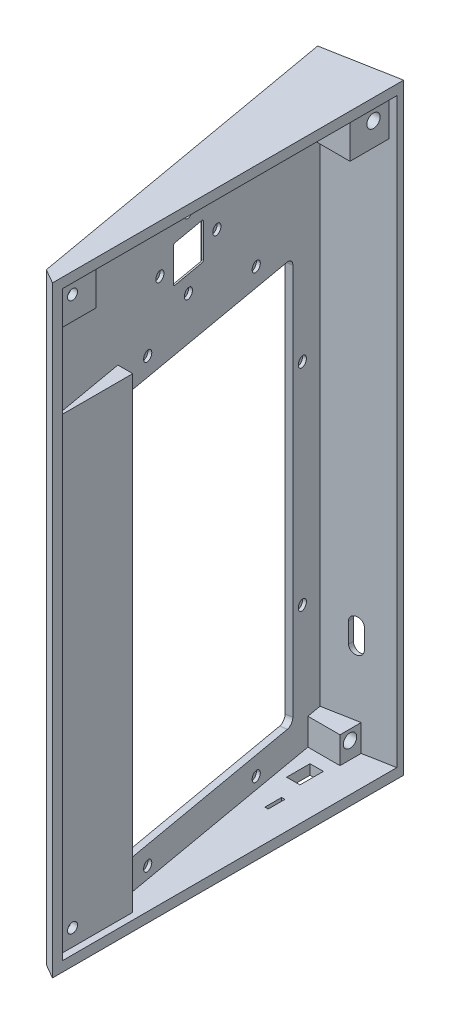
SolidWorks part; units mm, degrees
ref_plane "前视基准面" through (0, 0, 0) normal (0, 0, 1) x (1, 0, 0)
ref_plane "上视基准面" through (0, 0, 0) normal (0, 1, 0) x (1, 0, 0)
ref_plane "右视基准面" through (0, 0, 0) normal (1, 0, 0) x (0, 0, -1)
other "Configuration Table"
sketch "草图1" plane through (0, 0, 0) normal (0, 1, 0) x (1, 0, 0)
  line L0 (82.9035, -37.3993) -> (82.9035, -142.3993)
  line L1 (82.9035, -142.3993) -> (78.5734, -139.8993)
  line L2 (78.5734, -139.8993) -> (61.2086, -41.4185)
  line L3 (61.2086, -41.4185) -> (82.9035, -37.3993)
  dimension "D1" = 100
  dimension "D2" = 105
  dimension "D3" = 5
  dimension "D4" = 170
  dimension "D5" = 60
  dimension "D6" = 90.496
  dimension "D7" = 79.504
extrude "凸台-拉伸1" add sketch "草图1" along normal blind 180
sketch "草图5" plane through (52.2799, 0, -9.2184) normal (-0.9848, 0, 0.1736) x (0.1736, 0, 0.9848)
  line L0 (51.418, 180) -> (51.418, 0) construction
  line L1 (139.418, 12) -> (63.418, 12)
  line L2 (139.418, 12) -> (139.418, 133)
  line L3 (139.418, 133) -> (63.418, 133)
  line L4 (63.418, 12) -> (63.418, 133)
  line L5 (151.418, 180) -> (151.418, 0) construction
  line L6 (51.418, 0) -> (151.418, 0) construction
  dimension "D1" = 76
  dimension "D2" = 121
  dimension "D3" = 12
  dimension "D4" = 12
  dimension "D5" = 12
extrude "切除-拉伸2" cut sketch "草图5" against normal blind 2
sketch "草图7" plane through (82.9035, 0, 0) normal (1, 0, 0) x (0, 0, -1)
  line L8 (-139.3993, 3) -> (-40.3993, 3)
  line L9 (-40.3993, 3) -> (-40.3993, 177)
  line L10 (-40.3993, 177) -> (-139.3993, 177)
  line L11 (-139.3993, 177) -> (-139.3993, 3)
  line L12 (-139.3993, 3) -> (-40.3993, 3)
  line L13 (-40.3993, 3) -> (-40.3993, 177)
  line L14 (-40.3993, 177) -> (-139.3993, 177)
  line L15 (-139.3993, 177) -> (-139.3993, 3)
  dimension "D1" = 3
extrude "切除-拉伸3" cut sketch "草图7" against normal up to surface (19.8438 mm away)
sketch "草图10" plane through (54.2496, 0, -9.5657) normal (0.9848, 0, -0.1736) x (-0.1736, 0, -0.9848)
  line L1 (-63.418, 12) -> (-59.918, 12) construction
  line L2 (-63.418, 12) -> (-63.418, 41) construction
  line L3 (-63.418, 41) -> (-59.918, 41) construction
  line L4 (-59.918, 12) -> (-59.918, 41) construction
  line L5 (-63.418, 133) -> (-59.918, 133) construction
  line L6 (-63.418, 133) -> (-63.418, 104) construction
  line L7 (-63.418, 104) -> (-59.918, 104) construction
  line L8 (-59.918, 133) -> (-59.918, 104) construction
  circle A0 centre (-59.918, 104) radius 1.5
  circle A1 centre (-59.918, 41) radius 1.5
  dimension "D1" = 29
  dimension "D2" = 29
  dimension "D3" = 3.5
  dimension "D4" = 3.5
extrude "切除-拉伸5" cut sketch "草图10" against normal blind 1
sketch "草图11" plane through (54.2496, 0, -9.5657) normal (0.9848, 0, -0.1736) x (-0.1736, 0, -0.9848)
  line L0 (-76.918, 6.5) -> (-116.918, 6.5) construction
  line L1 (-63.418, 133) -> (-76.918, 133) construction
  line L2 (-63.418, 133) -> (-63.418, 138.5) construction
  line L3 (-63.418, 138.5) -> (-76.918, 138.5) construction
  line L4 (-76.918, 133) -> (-76.918, 138.5) construction
  line L5 (-63.418, 12) -> (-76.918, 12) construction
  line L6 (-63.418, 12) -> (-63.418, 6.5) construction
  line L7 (-63.418, 6.5) -> (-76.918, 6.5) construction
  line L8 (-76.918, 12) -> (-76.918, 6.5) construction
  line L9 (-76.918, 138.5) -> (-116.918, 138.5) construction
  circle A0 centre (-116.918, 138.5) radius 1.5
  circle A1 centre (-76.918, 138.5) radius 1.5
  circle A2 centre (-116.918, 6.5) radius 1.5
  circle A3 centre (-76.918, 6.5) radius 1.5
  dimension "D1" = 13.5
  dimension "D2" = 5.5
  dimension "D3" = 13.5
  dimension "D4" = 5.5
  dimension "D5" = 40
  dimension "D6" = 40
extrude "切除-拉伸6" cut sketch "草图11" against normal blind 1
sketch "草图12" plane through (82.9035, 0, 0) normal (1, 0, 0) x (0, 0, -1)
  line L1 (-139.3993, 3) -> (-116.3993, 3)
  line L2 (-139.3993, 3) -> (-139.3993, 142.5)
  line L3 (-139.3993, 142.5) -> (-116.3993, 142.5)
  line L4 (-116.3993, 3) -> (-116.3993, 142.5)
  line L6 (-127.7343, 133) -> (-52.8889, 133) construction
  dimension "D1" = 9.5
  dimension "D2" = 23
extrude "凸台-拉伸3" add sketch "草图12" against normal up to surface (2.3874 mm away)
sketch "草图13" plane through (54.2496, 0, -9.5657) normal (-0.9848, 0, 0.1736) x (0.1736, 0, 0.9848)
  line L4 (127.9081, 12) -> (139.418, 12)
  line L5 (139.418, 12) -> (139.418, 133)
  line L6 (139.418, 133) -> (127.9081, 133)
  line L7 (127.9081, 133) -> (127.9081, 12)
  line L8 (127.9081, 12) -> (139.418, 12)
  line L9 (139.418, 12) -> (139.418, 133)
  line L10 (139.418, 133) -> (127.9081, 133)
  line L11 (127.9081, 133) -> (127.9081, 12)
  dimension "D1" = 0
extrude "切除-拉伸7" cut sketch "草图13" against normal blind 2
sketch "草图14" plane through (52.2799, 0, -9.2184) normal (-0.9848, 0, 0.1736) x (0.1736, 0, 0.9848)
  line L0 (51.418, 180) -> (51.418, 0) construction
  line L1 (96.418, 151) -> (107.418, 151)
  line L2 (96.418, 151) -> (96.418, 162)
  line L3 (96.418, 162) -> (107.418, 162)
  line L4 (107.418, 151) -> (107.418, 162)
  line L5 (139.418, 133) -> (63.418, 133) construction
  line L6 (51.418, 180) -> (151.418, 180) construction
  dimension "D1" = 11
  dimension "D2" = 11
  dimension "D3" = 45
  dimension "D4" = 18
  dimension "D5" = 18
extrude "切除-拉伸8" cut sketch "草图14" against normal blind 2
sketch "草图17" plane through (9.4497, 0, 51.0074) normal (-0.1822, 0, -0.9833) x (-0.9833, 0, 0.1822)
  line L1 (-74.7037, 180) -> (-52.6396, 180)
  line L2 (-74.7037, 180) -> (-74.7037, 0)
  line L3 (-74.7037, 0) -> (-52.6396, 0)
  line L4 (-52.6396, 180) -> (-52.6396, 0)
extrude "凸台-拉伸9" add sketch "草图17" against normal blind 2
sketch "草图18" plane through (0, 0, 0) normal (0, -1, 0) x (1, 0, 0)
  line L0 (82.9035, 39.4333) -> (82.9035, 37.3993)
  line L1 (83.2679, 39.3658) -> (82.9035, 39.4333) construction
  line L2 (83.2679, 39.3658) -> (82.9035, 37.3993) construction
  line L3 (83.2679, 39.3658) -> (82.9035, 37.3993)
  line L4 (83.2679, 39.3658) -> (82.9035, 39.4333)
extrude "切除-拉伸9" cut sketch "草图18" against normal up to surface (180 mm away) up to face at (78.6267, 180, 73.3192)
sketch "草图19" plane through (0, 3, 0) normal (0, 1, 0) x (1, 0, 0)
  line L0 (82.9035, -40.3993) -> (82.9035, -36.7908) construction
  line L1 (77.596, -40.4166) -> (82.9035, -39.4333)
  line L2 (63.5225, -43.0238) -> (77.6894, -40.3993) construction
  line L3 (82.9035, -39.4333) -> (82.9035, -40.3993)
  line L4 (82.9035, -40.3993) -> (77.596, -40.4166)
extrude "切除-拉伸10" cut sketch "草图19" along normal up to surface (174 mm away) up to face at (77.507, 177, 80.5242)
sketch "草图20" plane through (82.9035, 0, 0) normal (1, 0, 0) x (0, 0, -1)
  line L1 (-139.3993, 142.5) -> (-116.3993, 142.5)
  line L2 (-139.3993, 142.5) -> (-139.3993, 3)
  line L3 (-139.3993, 3) -> (-116.3993, 3)
  line L4 (-116.3993, 142.5) -> (-116.3993, 3)
extrude "切除-拉伸11" cut sketch "草图20" against normal blind 2
sketch "草图21" plane through (54.2496, 0, -9.5657) normal (0.9848, 0, -0.1736) x (-0.1736, 0, -0.9848)
  line L0 (-107.418, 156.5) -> (-112.418, 156.5) construction
  line L1 (-107.418, 151) -> (-107.418, 162) construction
  line L2 (-101.918, 162) -> (-101.918, 167) construction
  line L3 (-107.418, 162) -> (-96.418, 162) construction
  line L4 (-96.418, 156.5) -> (-91.418, 156.5) construction
  line L5 (-96.418, 162) -> (-96.418, 151) construction
  line L6 (-101.918, 151) -> (-101.918, 146) construction
  line L7 (-96.418, 151) -> (-107.418, 151) construction
  circle A0 centre (-112.418, 156.5) radius 1.5
  circle A1 centre (-91.418, 156.5) radius 1.5
  circle A2 centre (-101.918, 146) radius 1.5
  circle A3 centre (-101.918, 167) radius 1.5
  dimension "D1" = 5
extrude "切除-拉伸12" cut sketch "草图21" against normal blind 1
sketch "草图23" plane through (80.9035, 0, 0) normal (1, 0, 0) x (0, 0, -1)
  line L0 (-51.4333, 8) -> (-51.4333, 26.4031) construction
  line L1 (-139.3993, 3) -> (-127.3993, 3)
  line L2 (-139.3993, 3) -> (-139.3993, 15)
  line L3 (-139.3993, 15) -> (-127.3993, 15)
  line L4 (-127.3993, 3) -> (-127.3993, 15)
  line L5 (-39.4333, 177) -> (-139.3993, 177) construction
  line L11 (-51.4333, 165) -> (-39.4333, 165)
  line L12 (-51.4333, 165) -> (-51.4333, 177)
  line L13 (-51.4333, 177) -> (-39.4333, 177)
  line L14 (-39.4333, 165) -> (-39.4333, 177)
  line L15 (-127.3993, 8) -> (-127.3993, 23.4787) construction
  line L17 (-127.3993, 165) -> (-139.3993, 165)
  line L18 (-127.3993, 165) -> (-127.3993, 177)
  line L19 (-127.3993, 177) -> (-139.3993, 177)
  line L20 (-139.3993, 165) -> (-139.3993, 177)
  dimension "D1" = 12
  dimension "D2" = 12
  dimension "D5" = 0
  dimension "D6" = 12
  dimension "D7" = 12
  dimension "D8" = 12
  dimension "D9" = 12
  dimension "D11" = 0
extrude "凸台-拉伸10" add sketch "草图23" against normal up to surface (0.3874 mm away)
fillet "圆角4" radius 2 5 edges at (64.2772, 133, 53.0625) (78.4592, 133, 127.7343) (64.2772, 12, 53.0625) (77.4744, 12, 127.9079) (80.394, 12, 127.3931)
sketch "草图26" plane through (0, 177, 0) normal (0, 1, 0) x (1, 0, 0)
  line L3 (63.1752, -41.0542) -> (71.9242, -39.4333)
  line L4 (71.9242, -39.4333) -> (62.8894, -39.4333)
  line L5 (62.8894, -39.4333) -> (63.1752, -41.0542)
  line L6 (63.1752, -41.0542) -> (71.9242, -39.4333)
  line L7 (71.9242, -39.4333) -> (62.8894, -39.4333)
  line L8 (62.8894, -39.4333) -> (63.1752, -41.0542)
  dimension "D1" = 0
extrude "切除-拉伸15" cut sketch "草图26" against normal up to next
sketch "草图27" plane through (82.9035, 0, 0) normal (1, 0, 0) x (0, 0, -1)
  line L1 (-39.4333, 3) -> (-47.4333, 3)
  line L2 (-39.4333, 3) -> (-39.4333, 11)
  line L3 (-39.4333, 11) -> (-47.4333, 11)
  line L4 (-47.4333, 3) -> (-47.4333, 11)
  dimension "D1" = 8
  dimension "D2" = 8
extrude "凸台-拉伸11" add sketch "草图27" against normal up to surface (18.6035 mm away)
sketch "草图28" plane through (82.9035, 0, 0) normal (1, 0, 0) x (0, 0, -1)
  line L1 (-47.4333, 3) -> (-39.4333, 3)
  line L2 (-47.4333, 3) -> (-47.4333, 11)
  line L3 (-47.4333, 11) -> (-39.4333, 11)
  line L4 (-39.4333, 3) -> (-39.4333, 11)
extrude "切除-拉伸16" cut sketch "草图28" against normal blind 9
sketch "草图29" plane through (0, 11, 0) normal (0, -1, 0) x (1, 0, 0)
  line L3 (73.9035, 41.1006) -> (73.9035, 39.4333)
  line L4 (73.9035, 39.4333) -> (82.9035, 39.4333)
  line L5 (82.9035, 39.4333) -> (73.9035, 41.1006)
  line L6 (73.9035, 41.1006) -> (73.9035, 39.4333)
  line L7 (73.9035, 39.4333) -> (82.9035, 39.4333)
  line L11 (82.9035, 39.4333) -> (73.9035, 41.1006)
  dimension "D1" = 0
extrude "凸台-拉伸12" add sketch "草图29" along normal up to surface (8 mm away) up to face at (77.0227, 3, 85.6663)
sketch "草图30" plane through (0, 3, 0) normal (0, -1, 0) x (1, 0, 0)
  line L3 (71.9242, 39.4333) -> (63.1752, 41.0542)
  line L4 (63.1752, 41.0542) -> (62.8894, 39.4333)
  line L5 (62.8894, 39.4333) -> (71.9242, 39.4333)
  line L6 (71.9242, 39.4333) -> (63.1752, 41.0542)
  line L7 (63.1752, 41.0542) -> (62.8894, 39.4333)
  line L8 (62.8894, 39.4333) -> (71.9242, 39.4333)
  dimension "D1" = 0
extrude "切除-拉伸17" cut sketch "草图30" against normal up to next
sketch "草图31" plane through (0, 0, 0) normal (0, -1, 0) x (1, 0, 0)
  line L1 (82.9035, 37.3993) -> (68.9035, 37.3993) construction
  line L2 (82.9035, 37.3993) -> (82.9035, 51.3993) construction
  line L3 (82.9035, 51.3993) -> (68.9035, 51.3993) construction
  line L4 (68.9035, 37.3993) -> (68.9035, 51.3993) construction
  line L5 (68.9035, 51.3993) -> (72.9035, 51.3993)
  line L6 (68.9035, 51.3993) -> (68.9035, 58.3993)
  line L7 (68.9035, 58.3993) -> (72.9035, 58.3993)
  line L8 (72.9035, 51.3993) -> (72.9035, 58.3993)
  dimension "D1" = 14
  dimension "D2" = 14
  dimension "D3" = 7
  dimension "D4" = 4
extrude "切除-拉伸18" cut sketch "草图31" against normal up to next
ref_plane "基准面1" through (0, 0, 37.3993) normal (0, 0, -1) x (-1, 0, 0)
ref_plane "基准面2" through (0, 0, 39.7193) normal (0, 0, -1) x (-1, 0, 0)
sketch "草图32" plane through (0, 0, 39.7193) normal (0, 0, -1) x (-1, 0, 0)
  line L0 (-72.7086, 36) -> (-72.7086, 30) construction
  line L1 (-70.7086, 36) -> (-70.7086, 30)
  line L2 (-74.7086, 36) -> (-74.7086, 30)
  line L3 (-82.9035, 180) -> (-61.2086, 180) construction
  line L4 (-61.2086, 180) -> (-61.2086, 0) construction
  arc A0 (-70.7086, 36) -> (-74.7086, 36) centre (-72.7086, 36) ccw
  arc A1 (-74.7086, 30) -> (-70.7086, 30) centre (-72.7086, 30) ccw
  point P2 (-72.7086, 33)
  point P9 (-72.7086, 28)
  point P10 (-72.7086, 38)
  dimension "D1" = 147
  dimension "D2" = 10
  dimension "D3" = 4
  dimension "D4" = 9.5
extrude "切除-拉伸23" cut sketch "草图32" against normal up to surface (1.9733 mm away)
ref_plane "基准面4" through (0, 0, 40.2193) normal (0, 0, -1) x (-1, 0, 0)
sketch "草图35" plane through (0, 0, 40.2193) normal (0, 0, -1) x (-1, 0, 0)
  line L0 (-74.7086, 36) -> (-74.7086, 30) construction
  line L1 (-76.7086, 41) -> (-68.7086, 41)
  line L2 (-76.7086, 41) -> (-76.7086, 25)
  line L3 (-76.7086, 25) -> (-68.7086, 25)
  line L4 (-68.7086, 41) -> (-68.7086, 25)
  line L5 (-70.7086, 30) -> (-70.7086, 36) construction
  arc A0 (-70.7086, 36) -> (-74.7086, 36) centre (-72.7086, 36) ccw construction
  arc A1 (-74.7086, 30) -> (-70.7086, 30) centre (-72.7086, 30) ccw construction
  dimension "D1" = 5
  dimension "D2" = 5
  dimension "D3" = 2
  dimension "D4" = 2
extrude "切除-拉伸25" cut sketch "草图35" along normal up to surface (0.1902 mm away)
fillet "圆角5" radius 0.5 4 edges at (76.7086, 25, 39.3831) (76.7086, 41, 39.3831) (68.7086, 25, 40.1241) (68.7086, 41, 40.1241)
sketch "草图36" plane through (0, 0, 0) normal (0, -1, 0) x (1, 0, 0)
  line L1 (82.9035, 37.3993) -> (74.4035, 37.3993) construction
  line L2 (82.9035, 37.3993) -> (82.9035, 64.3993) construction
  line L3 (82.9035, 64.3993) -> (74.4035, 64.3993) construction
  line L4 (74.4035, 37.3993) -> (74.4035, 64.3993) construction
  line L5 (74.4035, 64.3993) -> (73.4035, 64.3993)
  line L6 (74.4035, 64.3993) -> (74.4035, 69.3993)
  line L7 (74.4035, 69.3993) -> (73.4035, 69.3993)
  line L8 (73.4035, 64.3993) -> (73.4035, 69.3993)
  dimension "D1" = 8.5
  dimension "D2" = 27
  dimension "D3" = 1
  dimension "D4" = 5
extrude "切除-拉伸26" cut sketch "草图36" against normal up to next
sketch "草图37" plane through (0, 0, 0) normal (0, -1, 0) x (1, 0, 0)
  line L0 (73.4035, 66.8993) -> (74.4035, 66.8993) construction
  line L1 (73.4035, 69.3993) -> (73.4035, 64.3993) construction
  line L2 (74.4035, 64.3993) -> (74.4035, 69.3993) construction
  line L3 (73.9035, 64.3993) -> (73.9035, 69.3993) construction
  line L4 (73.4035, 64.3993) -> (74.4035, 64.3993) construction
  line L5 (74.4035, 69.3993) -> (73.4035, 69.3993) construction
  line L7 (74.9035, 69.8993) -> (72.9035, 69.8993)
  line L8 (74.9035, 69.8993) -> (74.9035, 63.8993)
  line L9 (74.9035, 63.8993) -> (72.9035, 63.8993)
  line L10 (72.9035, 69.8993) -> (72.9035, 63.8993)
  line L11 (74.9035, 69.8993) -> (72.9035, 63.8993) construction
  line L12 (74.9035, 63.8993) -> (72.9035, 69.8993) construction
  point P12 (73.9035, 66.8993)
  dimension "D1" = 6
  dimension "D2" = 2
extrude "切除-拉伸27" cut sketch "草图37" against normal blind 1
sketch "草图38" plane through (73.9035, 0, 0) normal (1, 0, 0) x (0, 0, -1)
  line L0 (-47.4333, 3) -> (-41.1006, 3) construction
  line L1 (-47.4333, 11) -> (-44.4333, 11) construction
  line L2 (-47.4333, 11) -> (-47.4333, 8) construction
  line L3 (-47.4333, 8) -> (-44.4333, 8) construction
  line L4 (-44.4333, 11) -> (-44.4333, 8) construction
  line L5 (-47.4333, 11) -> (-47.4333, 3) construction
  circle A0 centre (-44.4333, 8) radius 2
  dimension "D1" = 5
  dimension "D2" = 3
extrude "切除-拉伸28" cut sketch "草图38" against normal blind 3 contours A0
sketch "草图39" plane through (80.9035, 0, 0) normal (1, 0, 0) x (0, 0, -1)
  line L0 (-47.4333, 10.1358) -> (-47.4333, 2.8866) construction
  line L4 (-39.8038, 177) -> (-51.4333, 177) construction
  line L5 (-47.4333, 169) -> (-39.8038, 169) construction
  line L6 (-47.4333, 169) -> (-47.4333, 177) construction
  line L7 (-47.4333, 177) -> (-39.8038, 177) construction
  line L8 (-39.8038, 169) -> (-39.8038, 177) construction
  line L10 (-47.4333, 169) -> (-44.4333, 169) construction
  line L11 (-47.4333, 169) -> (-47.4333, 172) construction
  line L12 (-47.4333, 172) -> (-44.4333, 172) construction
  line L13 (-44.4333, 169) -> (-44.4333, 172) construction
  circle A0 centre (-44.4333, 172) radius 2
  dimension "D1" = 8
  dimension "D2" = 3
  dimension "D3" = 3
extrude "切除-拉伸30" cut sketch "草图39" against normal blind 3
sketch "草图40" plane through (80.9035, 0, 0) normal (1, 0, 0) x (0, 0, -1)
  line L1 (-127.3993, 177) -> (-131.3993, 177) construction
  line L2 (-127.3993, 177) -> (-127.3993, 171) construction
  line L3 (-127.3993, 171) -> (-131.3993, 171) construction
  line L4 (-131.3993, 177) -> (-131.3993, 171) construction
  line L5 (-131.3993, 171) -> (-134.3993, 171) construction
  line L6 (-131.3993, 171) -> (-131.3993, 172) construction
  line L7 (-131.3993, 172) -> (-134.3993, 172) construction
  line L8 (-134.3993, 171) -> (-134.3993, 172) construction
  line L9 (-139.3993, 3) -> (-134.3993, 3) construction
  line L10 (-139.3993, 3) -> (-139.3993, 8) construction
  line L11 (-139.3993, 8) -> (-134.3993, 8) construction
  line L12 (-134.3993, 3) -> (-134.3993, 8) construction
  circle A0 centre (-134.3993, 172) radius 1.5
  circle A1 centre (-134.3993, 8) radius 1.5
  dimension "D5" = 5
  dimension "D1" = 6
  dimension "D2" = 4
  dimension "D3" = 3
  dimension "D4" = 1
  dimension "D6" = 5
extrude "切除-拉伸31" cut sketch "草图40" against normal blind 2
sketch "草图42" plane through (54.2496, 0, -9.5657) normal (-0.9848, 0, 0.1736) x (0.1736, 0, 0.9848)
  line L3 (139.0778, 15) -> (139.0778, 12.8842)
  line L4 (139.418, 14) -> (139.418, 15)
  line L5 (139.418, 15) -> (139.0778, 15)
  line L6 (139.0778, 15) -> (139.0778, 12.8842)
  line L7 (139.418, 14) -> (139.418, 15)
  line L8 (139.418, 15) -> (139.0778, 15)
  arc A1 (139.0778, 12.8842) -> (139.418, 14) centre (137.418, 14) ccw
  arc A2 (139.0778, 12.8842) -> (139.418, 14) centre (137.418, 14) ccw
  dimension "D1" = 0
extrude "切除-拉伸34" cut sketch "草图42" against normal up to surface (2 mm away) up to face at (79.6913, 72.5, 123.2038)
chamfer "倒角1" distance 2 distance2 1.5 4 edges at (69.9778, 151, 91.1513) (69.0228, 156.5, 85.7348) (69.9778, 162, 91.1513) (70.9329, 156.5, 96.5677)
fillet "圆角6" radius 0.5 4 edges at (72.6563, 151, 96.2638) (72.6563, 162, 96.2638) (70.7462, 162, 85.431) (70.7462, 151, 85.431)
